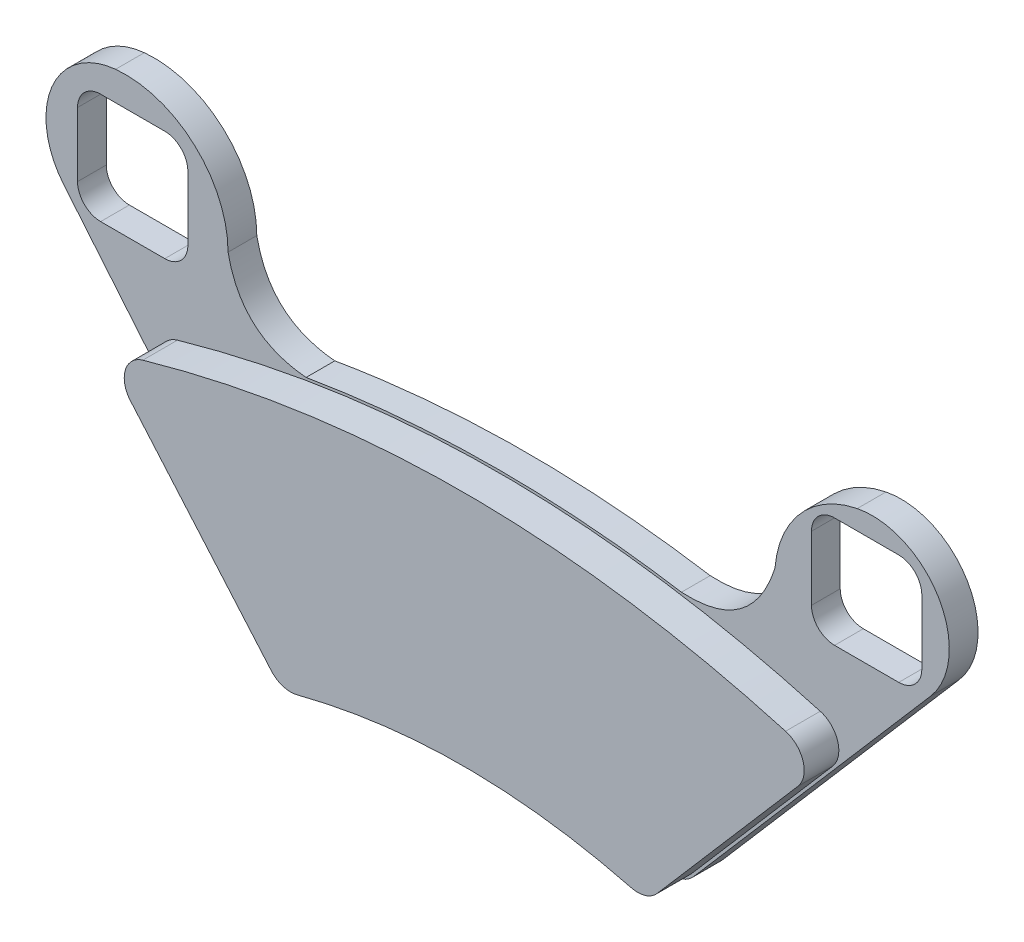
SolidWorks part; units mm, degrees
ref_plane "Front Plane" through (0, 0, 0) normal (0, 0, 1) x (1, 0, 0)
ref_plane "Top Plane" through (0, 0, 0) normal (0, 1, 0) x (1, 0, 0)
ref_plane "Right Plane" through (0, 0, 0) normal (1, 0, 0) x (0, 0, -1)
sketch "Sketch1" plane through (0, 0, 0) normal (0, 0, 1) x (1, 0, 0)
  line L0 (-17.8392, 0) -> (18.2796, 0) construction
  line L1 (0, 0) -> (0, 2.54) construction
  line L2 (-17.8392, 0) -> (-35.3652, 0) construction
  line L3 (-35.3652, 0) -> (-35.3652, 20.32) construction
  line L4 (-35.3652, 20.32) -> (-17.8392, 0) construction
  line L5 (-35.3652, 20.32) -> (-17.8392, 0)
  line L6 (18.2796, 0) -> (35.8056, 0) construction
  line L7 (35.8056, 0) -> (35.8056, 20.32) construction
  line L8 (18.2796, 0) -> (35.8056, 20.32)
  line L9 (0, 2.54) -> (0, 26.0096) construction
  line L10 (35.8056, 20.32) -> (-35.3652, 20.32) construction
  spline S0 degree 2 poles (-17.8392, 0) (0.2117, 5.0807) (18.2796, 0) knots 0 0 0 1 1 1
  spline S1 degree 2 poles (-35.3652, 20.32) (0.2093, 31.6996) (35.8056, 20.32) knots 0 0 0 1 1 1
  dimension "D1" = 36.1188
  dimension "D2" = 2.54
  dimension "D3" = 17.526
  dimension "D4" = 20.32
  dimension "D5" = 17.526
  dimension "D6" = 23.4696
  dimension "D7" = 71.1708
extrude "Boss-Extrude1" add sketch "Sketch1" along normal blind 3.429
fillet "Fillet1" radius 2.54 4 edges at (18.2796, 0, 1.7145) (35.8056, 20.32, 1.7145) (-17.8392, 0, 1.7145) (-35.3652, 20.32, 1.7145)
sketch "Sketch3" plane through (0, 0, 0) normal (0, 0, -1) x (-1, 0, 0)
  line L0 (31.6393, 21.7135) -> (29.897, 22.1978) construction
  line L4 (-19.5146, 1.0429) -> (-22.7488, 2.8986) construction
  line L5 (33.5681, 19.8213) -> (24.8305, 21.6926) construction
  line L6 (-33.4468, 17.1962) -> (-19.5146, 1.0429)
  line L7 (19.0743, 1.0432) -> (33.0068, 17.1967)
  line L8 (-33.4468, 17.1962) -> (-19.5146, 1.0429)
  line L9 (19.0743, 1.0432) -> (33.0068, 17.1967)
  line L10 (33.5681, 19.8213) -> (33.5681, 30.2353) construction
  line L12 (33.5681, 30.2353) -> (37.1241, 30.2353) construction
  arc A12 (-19.5146, 1.0429) -> (-16.7017, 0.1621) centre (-17.3988, 2.8677) ccw
  arc A13 (16.261, 0.1625) -> (19.0743, 1.0432) centre (16.9586, 2.868) ccw
  arc A14 (33.0068, 17.1967) -> (31.6591, 21.7079) centre (30.891, 19.0216) ccw
  arc A15 (-32.0988, 21.7075) -> (-33.4468, 17.1962) centre (-31.3311, 19.0211) ccw
  arc A16 (-19.5146, 1.0429) -> (-16.7017, 0.1621) centre (-17.3988, 2.8677) ccw
  arc A17 (16.261, 0.1625) -> (19.0743, 1.0432) centre (16.9586, 2.868) ccw
  arc A18 (33.0068, 17.1967) -> (31.6591, 21.7079) centre (30.891, 19.0216) ccw
  arc A19 (-32.0988, 21.7075) -> (-33.4468, 17.1962) centre (-31.3311, 19.0211) ccw
  spline S0 degree 3 poles (-1066.0536, 1478.7335) (-431.195, -2300.6948) (-313.652, 1.9551) (1.0996, 2.2878) (2.4865, 2.2444) (5.2681, 2.0663) (6.6634, 1.9312) (219.3577, -25.5651) (253.6705, -1077.5588) (950.1209, 1703.7027) knots -27.820917 -27.820917 -27.820917 -27.820917 0.5 0.5 0.625 0.625 0.75 0.75 19.837527 19.837527 19.837527 19.837527 only from (-16.7017, 0.1621) to (16.261, 0.1625)
  spline S1 degree 3 poles (1120.576, 142.4025) (532.5297, -1804.9097) (369.0637, 25.9043) (-1.4509, 26.2651) (-2.7983, 26.2421) (-5.4988, 26.1468) (-6.8541, 26.0744) (-10.9093, 25.7839) (-13.596, 25.4931) (-336.224, -20.93) (-423.447, -1408.8326) (-1239.1185, 1403.2355) knots -16.658084 -16.658084 -16.658084 -16.658084 0.5 0.5 0.5625 0.5625 0.625 0.625 0.75 0.75 15.72696 15.72696 15.72696 15.72696 only from (31.6591, 21.7079) to (-32.0988, 21.7075)
  spline S2 degree 3 poles (-16.7017, 0.1621) (-11.2874, 1.557) (-5.816, 2.2805) (1.0996, 2.2878) (2.4865, 2.2444) (5.2681, 2.0663) (6.6634, 1.9312) (10.8149, 1.3945) (13.5522, 0.8609) (16.261, 0.1625) knots 0 0 0 0 0.5 0.5 0.625 0.625 0.75 0.75 1 1 1 1
  spline S3 degree 3 poles (31.6591, 21.7079) (21.235, 24.6884) (10.6518, 26.2533) (-1.4509, 26.2651) (-2.7983, 26.2421) (-5.4988, 26.1468) (-6.8541, 26.0744) (-10.9093, 25.7839) (-13.596, 25.4931) (-21.6072, 24.3404) (-26.8832, 23.198) (-32.0988, 21.7075) knots 0 0 0 0 0.5 0.5 0.5625 0.5625 0.625 0.625 0.75 0.75 1 1 1 1
  dimension "D2" = 8.7376
  dimension "D4" = 10.414
  dimension "D5" = 3.556
  dimension "D1" = 0.254
extrude "Boss-Extrude2" add sketch "Sketch3" along normal blind 2.8448
sketch "Sketch5" plane through (0, 0, 0) normal (0, 0, 1) x (1, 0, 0)
  line L0 (-33.685, 19.0216) -> (-33.685, 30.7056) construction
  line L1 (-39.8892, 36.0904) -> (-32.6756, 36.0904)
  line L2 (-41.6672, 34.3124) -> (-41.6672, 27.0988)
  line L3 (-39.8892, 25.3208) -> (-32.6756, 25.3208)
  line L4 (-30.8976, 34.3124) -> (-30.8976, 27.0988)
  line L5 (-41.6672, 36.0904) -> (-30.8976, 25.3208) construction
  line L6 (-41.6672, 25.3208) -> (-30.8976, 36.0904) construction
  line L7 (0.108, 2.5403) -> (0.108, 46.0656) construction
  line L8 (41.8831, 25.3208) -> (31.1135, 36.0904) construction
  line L9 (41.8831, 36.0904) -> (31.1135, 25.3208) construction
  line L10 (31.1135, 34.3124) -> (31.1135, 27.0988)
  line L11 (40.1051, 25.3208) -> (32.8915, 25.3208)
  line L12 (41.8831, 34.3124) -> (41.8831, 27.0988)
  line L13 (40.1051, 36.0904) -> (32.8915, 36.0904)
  line L14 (-33.685, 30.7056) -> (-36.2824, 30.7056) construction
  arc A0 (-41.6672, 27.0988) -> (-39.8892, 25.3208) centre (-39.8892, 27.0988) ccw
  arc A1 (-32.6756, 25.3208) -> (-30.8976, 27.0988) centre (-32.6756, 27.0988) ccw
  arc A2 (-32.6756, 36.0904) -> (-30.8976, 34.3124) centre (-32.6756, 34.3124) cw
  arc A3 (-39.8892, 36.0904) -> (-41.6672, 34.3124) centre (-39.8892, 34.3124) ccw
  arc A4 (-31.6591, 21.7079) -> (-33.0068, 17.1967) centre (-30.891, 19.0216) ccw construction
  arc A5 (40.1051, 36.0904) -> (41.8831, 34.3124) centre (40.1051, 34.3124) cw
  arc A6 (32.8915, 36.0904) -> (31.1135, 34.3124) centre (32.8915, 34.3124) ccw
  arc A7 (32.8915, 25.3208) -> (31.1135, 27.0988) centre (32.8915, 27.0988) cw
  arc A8 (41.8831, 27.0988) -> (40.1051, 25.3208) centre (40.1051, 27.0988) cw
  parabola Q0 (-16.3244, 0.4085) -> (16.7651, 0.408) focus (0.162, -29.5555) apex (0.108, 2.5403) construction
  parabola Q1 (-16.3244, 0.4085) -> (16.7651, 0.408) focus (0.162, -29.5555) apex (0.108, 2.5403) construction
  point P0 (-36.2824, 30.7056)
  point P48 (36.4983, 30.7056)
  point P49 (0, 0)
  dimension "D2" = 1.778
  dimension "D1" = 10.7696
  dimension "D3" = 11.684
  dimension "D4" = 2.5973
sketch "Sketch6" plane through (0, 0, -2.8448) normal (0, 0, -1) x (-1, 0, 0)
  line L0 (33.5681, 19.8213) -> (33.5681, 31.5053) construction
  line L1 (18.86, 24.6327) -> (22.7731, 23.8945)
  line L2 (33.5681, 31.5053) -> (36.7431, 31.5053) construction
  line L3 (30.9021, 14.7566) -> (46.6514, 33.7528) construction
  line L4 (19.0743, 1.0432) -> (33.0068, 17.1967) construction
  line L6 (22.7731, 25.7517) -> (22.7731, 23.8945) construction
  line L7 (46.6514, 33.7528) -> (30.9021, 14.7566)
  line L10 (22.7731, 23.8945) -> (30.9021, 14.7566)
  arc A0 (33.0068, 17.1967) -> (31.6591, 21.7079) centre (30.891, 19.0216) ccw construction
  arc A1 (46.6514, 33.7528) -> (26.5831, 31.5053) centre (36.7431, 31.5053) ccw
  spline S0 degree 3 poles (31.6591, 21.7079) (21.235, 24.6884) (10.6518, 26.2533) (-1.4509, 26.2651) (-2.7983, 26.2421) (-5.4988, 26.1468) (-6.8541, 26.0744) (-10.9093, 25.7839) (-13.596, 25.4931) (-21.6072, 24.3404) (-26.8832, 23.198) (-32.0988, 21.7075) knots 0 0 0 0 0.5 0.5 0.5625 0.5625 0.625 0.625 0.75 0.75 1 1 1 1 construction
  spline S1 degree 2 poles (26.5831, 31.5053) (25.304, 25.1986) (18.86, 24.6327) knots 0 0 0 1 1 1
  point P12 (24.0687, 26.6842)
  point P18 (18.86, 24.6327)
  dimension "D3" = 20.32
  dimension "D1" = 11.684
  dimension "D2" = 3.175
extrude "Boss-Extrude3" add sketch "Sketch6" against normal blind 2.8448
fillet "Fillet2" radius 7.62 1 edges at (-46.6514, 33.7528, -1.4224)
sketch "Sketch8" plane through (0, 0, -2.8448) normal (0, 0, -1) x (-1, 0, 0)
  line L2 (32.8461, 38.7443) -> (39.1961, 38.7443)
  line L3 (30.5601, 36.4583) -> (30.5601, 30.1083)
  line L4 (32.8461, 27.8223) -> (39.1961, 27.8223)
  line L5 (41.4821, 36.4583) -> (41.4821, 30.1083)
  line L6 (30.5601, 38.7443) -> (41.4821, 27.8223) construction
  line L7 (30.5601, 27.8223) -> (41.4821, 38.7443) construction
  arc A0 (30.5601, 30.1083) -> (32.8461, 27.8223) centre (32.8461, 30.1083) ccw
  arc A1 (39.1961, 27.8223) -> (41.4821, 30.1083) centre (39.1961, 30.1083) ccw
  arc A2 (39.1961, 38.7443) -> (41.4821, 36.4583) centre (39.1961, 36.4583) cw
  arc A3 (32.8461, 38.7443) -> (30.5601, 36.4583) centre (32.8461, 36.4583) ccw
  point P2 (36.0211, 33.2833)
  dimension "D4" = 2.286
  dimension "D1" = 10.922
  dimension "D2" = 1.778
  dimension "D3" = 0.722
extrude "Cut-Extrude1" cut sketch "Sketch8" against normal blind 2.8448
sketch "Sketch9" plane through (0, 0, -2.8448) normal (0, 0, -1) x (-1, 0, 0)
  line L0 (-34.1251, 19.0211) -> (-34.1251, 30.7051) construction
  line L1 (-34.1251, 30.7051) -> (-37.6811, 30.7051) construction
  line L2 (-19.5146, 1.0429) -> (-51.1405, 37.7107) construction
  line L3 (-47.4638, 33.4479) -> (-33.4468, 17.1962)
  line L4 (-33.4468, 17.1962) -> (-23.2533, 23.8848)
  arc A1 (-32.0988, 21.7075) -> (-33.4468, 17.1962) centre (-31.3311, 19.0211) ccw construction
  arc A2 (-27.5526, 31.5053) -> (-47.4638, 33.4479) centre (-37.6811, 30.7051) ccw
  spline S0 degree 3 poles (18.8595, 24.6327) (12.5969, 25.7041) (6.2761, 26.2574) (-1.4509, 26.265) (-2.7983, 26.242) (-5.4988, 26.1467) (-6.8541, 26.0743) (-10.9093, 25.7838) (-13.596, 25.4931) (-21.6072, 24.3404) (-26.8832, 23.198) (-32.0988, 21.7075) knots 0.203367 0.203367 0.203367 0.203367 0.5 0.5 0.5625 0.5625 0.625 0.625 0.75 0.75 1 1 1 1 construction
  spline S1 degree 2 poles (-27.5526, 31.5053) (-25.2683, 24.406) (-18.2928, 24.7989) knots 0 0 0 1 1 1
  spline S2 degree 1 poles (-23.2533, 23.8848) (-18.2928, 24.7989) knots 0 0 1 1
  dimension "D1" = 11.684
  dimension "D2" = 3.556
  dimension "D4" = 12.192
extrude "Boss-Extrude4" add sketch "Sketch9" against normal blind 2.8448
sketch "Sketch10" plane through (0, 0, -2.8448) normal (0, 0, -1) x (-1, 0, 0)
  line L0 (-39.7979, 38.7443) -> (-33.4479, 38.7443)
  line L1 (-31.1619, 36.4583) -> (-31.1619, 30.1083)
  line L2 (-33.4479, 27.8223) -> (-39.7979, 27.8223)
  line L3 (-42.0839, 30.1083) -> (-42.0839, 36.4583)
  line L4 (39.1961, 38.7443) -> (32.8461, 38.7443) construction
  line L5 (30.5601, 36.4583) -> (30.5601, 30.1083) construction
  arc A0 (-39.7979, 27.8223) -> (-42.0839, 30.1083) centre (-39.7979, 30.1083) cw
  arc A1 (-33.4479, 38.7443) -> (-31.1619, 36.4583) centre (-33.4479, 36.4583) cw
  arc A2 (-31.1619, 30.1083) -> (-33.4479, 27.8223) centre (-33.4479, 30.1083) cw
  arc A3 (-39.7979, 38.7443) -> (-42.0839, 36.4583) centre (-39.7979, 36.4583) ccw
  dimension "D3" = 2.286
  dimension "D1" = 10.922
  dimension "D2" = 61.722
extrude "Cut-Extrude2" cut sketch "Sketch10" against normal blind 2.8448
fillet "Fillet3" radius 7.62 1 edges at (47.4638, 33.4479, -1.4224)
sketch "Sketch11" plane through (0, 0, -2.8448) normal (0, 0, -1) x (-1, 0, 0)
  line L12 (-32.966, 17.611) -> (-19.0337, 1.4576)
  line L13 (18.5935, 1.4579) -> (32.5259, 17.6115)
  line L14 (-32.966, 17.611) -> (-19.0337, 1.4576)
  line L15 (18.5935, 1.4579) -> (32.5259, 17.6115)
  arc A24 (-19.0337, 1.4576) -> (-16.8601, 0.777) centre (-17.3988, 2.8677) ccw
  arc A25 (-31.9243, 21.097) -> (-32.966, 17.611) centre (-31.3311, 19.0211) ccw
  arc A26 (32.5259, 17.6115) -> (31.4845, 21.0974) centre (30.891, 19.0216) ccw
  arc A27 (16.4195, 0.7774) -> (18.5935, 1.4579) centre (16.9586, 2.868) ccw
  arc A28 (-19.0337, 1.4576) -> (-16.8601, 0.777) centre (-17.3988, 2.8677) ccw
  arc A29 (-31.9243, 21.097) -> (-32.966, 17.611) centre (-31.3311, 19.0211) ccw
  arc A30 (32.5259, 17.6115) -> (31.4845, 21.0974) centre (30.891, 19.0216) ccw
  arc A31 (16.4195, 0.7774) -> (18.5935, 1.4579) centre (16.9586, 2.868) ccw
  spline S4 degree 3 poles (-1236.9775, 2443.5374) (-454.0568, -2728.8724) (-343.299, 2.5596) (1.1124, 2.9228) (2.5126, 2.879) (5.321, 2.6992) (6.7297, 2.5629) (243.8184, -28.0803) (261.4565, -1321.0623) (1191.7702, 2670.3055) knots -30.205017 -30.205017 -30.205017 -30.205017 0.5 0.5 0.625 0.625 0.75 0.75 21.837133 21.837133 21.837133 21.837133 only from (-16.8601, 0.777) to (16.4195, 0.7774)
  spline S5 degree 3 poles (1379.0549, 1186.2334) (569.289, -2315.1885) (416.0881, 25.2235) (-1.4441, 25.6301) (-2.7842, 25.6072) (-5.4699, 25.5124) (-6.8178, 25.4404) (-10.8508, 25.1514) (-13.5228, 24.8622) (-365.2408, -25.755) (-435.7347, -1681.9516) (-1497.5491, 2376.8678) knots -18.950133 -18.950133 -18.950133 -18.950133 0.5 0.5 0.5625 0.5625 0.625 0.625 0.75 0.75 17.179257 17.179257 17.179257 17.179257 only from (31.4845, 21.0974) to (-31.9243, 21.097)
  spline S6 degree 3 poles (-16.8601, 0.777) (-11.3938, 2.1854) (-5.8697, 2.9154) (1.1124, 2.9228) (2.5126, 2.879) (5.321, 2.6992) (6.7297, 2.5629) (10.9211, 2.0211) (13.6847, 1.4825) (16.4195, 0.7774) knots 0 0 0 0 0.5 0.5 0.625 0.625 0.75 0.75 1 1 1 1
  spline S7 degree 3 poles (31.4845, 21.0974) (21.1175, 24.0616) (10.5923, 25.6183) (-1.4441, 25.6301) (-2.7842, 25.6072) (-5.4699, 25.5124) (-6.8178, 25.4404) (-10.8508, 25.1514) (-13.5228, 24.8622) (-21.4901, 23.7156) (-26.7372, 22.5793) (-31.9243, 21.097) knots 0 0 0 0 0.5 0.5 0.5625 0.5625 0.625 0.625 0.75 0.75 1 1 1 1
  dimension "D2" = 0.381
extrude "Boss-Extrude5" add sketch "Sketch11" along normal blind 0.0254
